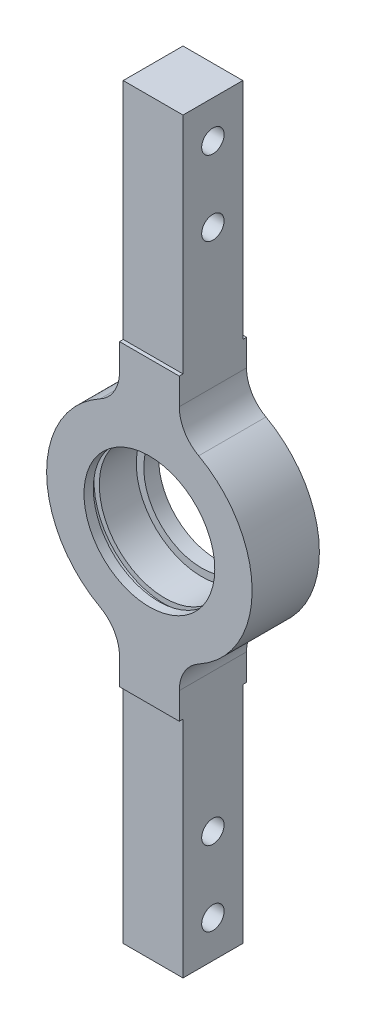
SolidWorks part; units mm, degrees
material "1060 Alloy"
ref_plane "Front Plane" through (0, 0, 0) normal (0, 0, 1) x (1, 0, 0)
ref_plane "Top Plane" through (0, 0, 0) normal (0, 1, 0) x (1, 0, 0)
ref_plane "Right Plane" through (0, 0, 0) normal (1, 0, 0) x (0, 0, -1)
sketch "Sketch1" plane through (0, 0, 0) normal (0, 0, 1) x (1, 0, 0)
  circle A0 centre (0, 0) radius 15.5
  circle A1 centre (0, 0) radius 27.5
  dimension "D1" = 31
  dimension "D2" = 55
extrude "Boss-Extrude1" add sketch "Sketch1" along normal mid plane 18
sketch "Sketch2" plane through (0, 0, 0) normal (0, 0, 1) x (1, 0, 0)
  line L0 (0, 0) -> (0, 74.602) construction
  line L1 (-8, 100) -> (8, 100)
  line L2 (8, 100) -> (8, 26.3106)
  line L3 (8, 26.3106) -> (0, 27.5)
  line L4 (-8, 26.3106) -> (0, 27.5)
  line L5 (-8, 100) -> (-8, 26.3106)
  circle A0 centre (0, 0) radius 27.5 construction
  point P11 (0, 100)
  dimension "D1" = 16
  dimension "D2" = 100
extrude "Boss-Extrude2" add sketch "Sketch2" along normal mid plane 18
mirror "Mirror1" about plane through (0, 0, 0) normal (0, 1, 0) of "Boss-Extrude2"
sketch "Sketch3" plane through (0, 0, 0) normal (1, 0, 0) x (0, 0, -1)
  line L0 (0, 0) -> (53.684, 0) construction
  line L1 (5, 15.5) -> (5, 17.5)
  line L2 (9, 15.5) -> (-9, 15.5) construction
  line L3 (5, 17.5) -> (-9, 17.5)
  line L4 (-9, 26.3106) -> (-9, -26.3106) construction
  line L5 (-9, 17.5) -> (-9, 15.5)
  line L6 (-9, 15.5) -> (5, 15.5)
  dimension "D1" = 17.5
  dimension "D2" = 5
revolve "Cut-Revolve1" cut sketch "Sketch3" angle 360 about L0
sketch "Sketch4" plane through (0, 0, 0) normal (1, 0, 0) x (0, 0, -1)
  line L0 (0, 0) -> (21.5903, 0) construction
  line L1 (-4.9, 17) -> (-4.9, 18.9)
  line L2 (-4.9, 18.9) -> (-6.5, 18.9)
  line L3 (-6.5, 18.9) -> (-6.5, 17)
  line L4 (-6.5, 17) -> (-4.9, 17)
  line L5 (5, 17.5) -> (5, -17.5) construction
  dimension "D1" = 11.5
  dimension "D2" = 1.6
  dimension "D3" = 18.9
  dimension "D4" = 17
revolve "Cut-Revolve2" cut sketch "Sketch4" angle 360 about L0
fillet "Fillet1" radius 10 4 edges at (8, -26.3106, 0) (-8, -26.3106, 0) (-8, 26.3106, 0) (8, 26.3106, 0)
sketch "Sketch5" plane through (0, -100, 0) normal (0, -1, 0) x (1, 0, 0)
  line L0 (8, 9) -> (8, -9) construction
  line L1 (-8, 9) -> (8, 9)
  line L2 (-8, 9) -> (-8, 8)
  line L3 (-8, 8) -> (8, 8)
  line L4 (8, 9) -> (8, 8)
  line L6 (-8, -9) -> (8, -9)
  line L7 (-8, -9) -> (-8, -8)
  line L8 (-8, -8) -> (8, -8)
  line L9 (8, -9) -> (8, -8)
  dimension "D1" = 1
  dimension "D2" = 1
extrude "Cut-Extrude1" cut sketch "Sketch5" against normal blind 60
sketch "Sketch6" plane through (-8, 0, 0) normal (-1, 0, 0) x (0, 0, 1)
  line L0 (0, 0) -> (0, 105.7875) construction
  line L1 (9, 100) -> (-9, 100) construction
  circle A0 centre (0, 90) radius 3
  circle A1 centre (0, 70) radius 3
  dimension "D1" = 6
  dimension "D2" = 6
  dimension "D3" = 10
  dimension "D4" = 20
extrude "Cut-Extrude2" cut sketch "Sketch6" against normal through all
sketch "Sketch7" plane through (-8, 0, 0) normal (-1, 0, 0) x (0, 0, 1)
  line L0 (0, 0) -> (0, -107.0143) construction
  line L1 (8, -100) -> (-8, -100) construction
  circle A0 centre (0, -90) radius 3
  circle A1 centre (0, -70) radius 3
  dimension "D1" = 6
  dimension "D2" = 6
  dimension "D3" = 10
  dimension "D4" = 20
extrude "Cut-Extrude3" cut sketch "Sketch7" against normal through all
mirror "Mirror2" about plane through (0, 0, 0) normal (0, 1, 0) of "Cut-Extrude1"
